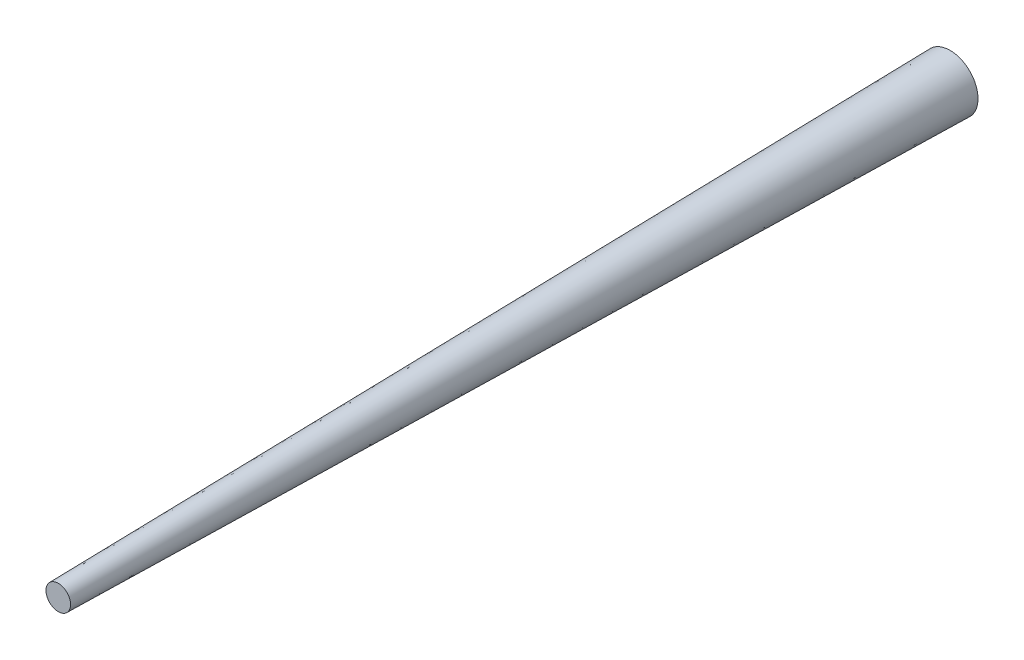
SolidWorks part; units mm, degrees
ref_plane "Plano frontal" through (0, 0, 0) normal (0, 0, 1) x (1, 0, 0)
ref_plane "Plano superior" through (0, 0, 0) normal (0, 1, 0) x (1, 0, 0)
ref_plane "Plano direito" through (0, 0, 0) normal (1, 0, 0) x (0, 0, -1)
sketch "Esboço1" plane through (0, 0, 0) normal (0, 0, 1) x (1, 0, 0)
  circle A0 centre (0, 0) radius 5
extrude "Ressalto-extrusão1" add sketch "Esboço1" along normal blind 160 draft 1
